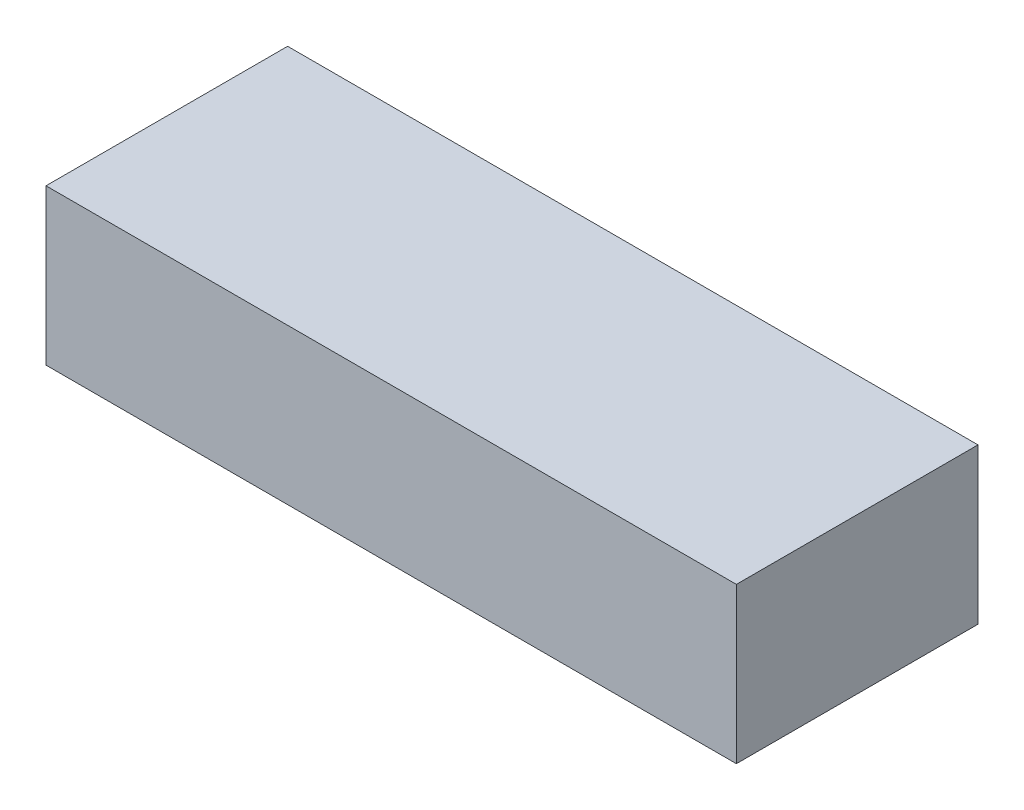
SolidWorks part; units mm, degrees
ref_plane "前视基准面" through (0, 0, 0) normal (0, 0, 1) x (1, 0, 0)
ref_plane "上视基准面" through (0, 0, 0) normal (0, 1, 0) x (1, 0, 0)
ref_plane "右视基准面" through (0, 0, 0) normal (1, 0, 0) x (0, 0, -1)
sketch "草图1" plane through (0, 0, 0) normal (0, 1, 0) x (1, 0, 0)
  line L1 (-20, 7) -> (20, 7)
  line L2 (-20, 7) -> (-20, -7)
  line L3 (-20, -7) -> (20, -7)
  line L4 (20, 7) -> (20, -7)
  line L5 (0, -7) -> (0, 7) construction
  line L6 (-20, 0) -> (20, 0) construction
  point P0 (0, 0)
  dimension "D1" = 40
  dimension "D2" = 14
extrude "凸台-拉伸1" add sketch "草图1" along normal blind 9
